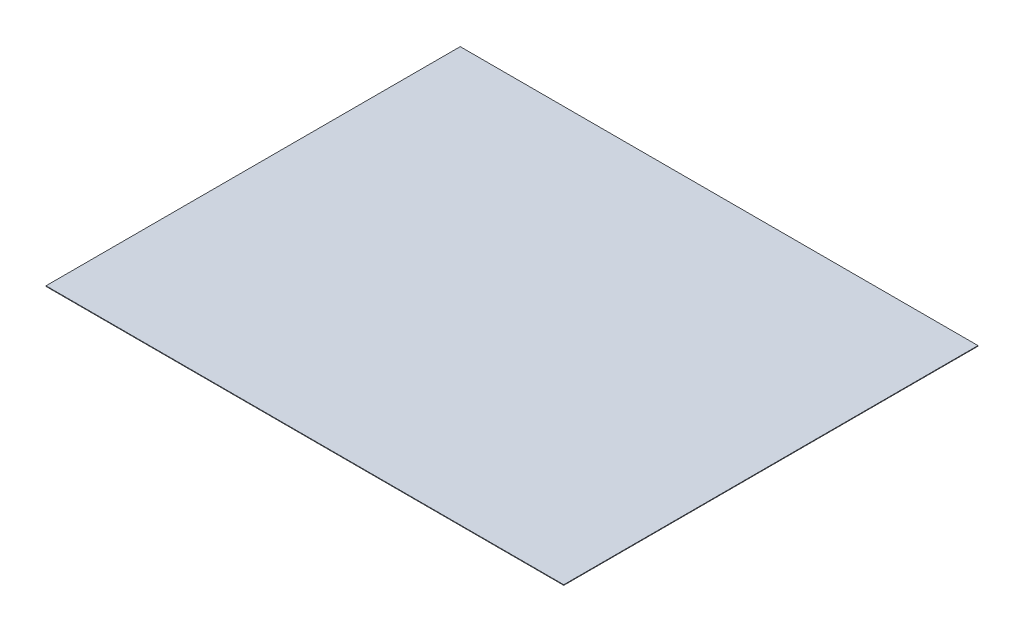
SolidWorks part; units mm, degrees
ref_plane "Front" through (0, 0, 0) normal (0, 0, 1) x (1, 0, 0)
ref_plane "Top" through (0, 0, 0) normal (0, 1, 0) x (1, 0, 0)
ref_plane "Right" through (0, 0, 0) normal (1, 0, 0) x (0, 0, -1)
sketch "Sketch1" plane through (0, 0, 0) normal (0, 1, 0) x (1, 0, 0)
  line L1 (-4572, -3657.6) -> (4572, -3657.6)
  line L2 (-4572, -3657.6) -> (-4572, 3657.6)
  line L3 (-4572, 3657.6) -> (4572, 3657.6)
  line L4 (4572, -3657.6) -> (4572, 3657.6)
  line L5 (-4572, -3657.6) -> (4572, 3657.6) construction
  line L6 (-4572, 3657.6) -> (4572, -3657.6) construction
  point P0 (0, 0)
  dimension "D1" = 7315.2
  dimension "D2" = 9144
extrude "Boss-Extrude1" add sketch "Sketch1" along normal blind 10
